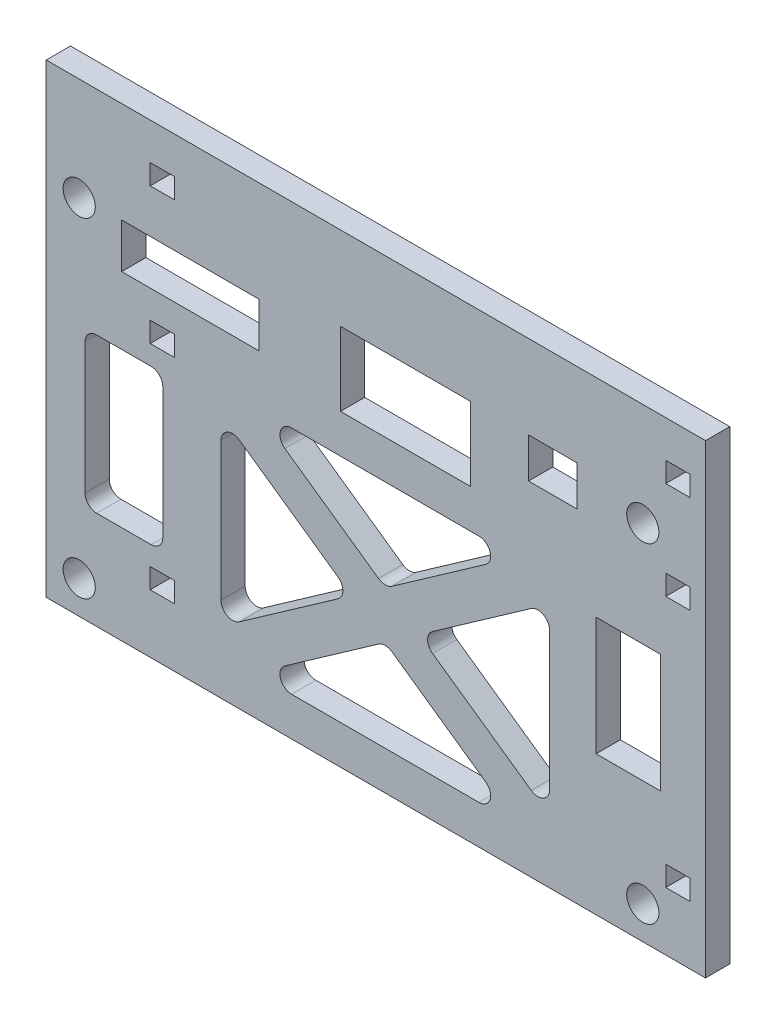
SolidWorks part; units mm, degrees
material "Beech"
ref_plane "Front Plane" through (0, 0, 0) normal (0, 0, 1) x (1, 0, 0)
ref_plane "Top Plane" through (0, 0, 0) normal (0, 1, 0) x (1, 0, 0)
ref_plane "Right Plane" through (0, 0, 0) normal (1, 0, 0) x (0, 0, -1)
sketch "Sketch1" plane through (0, 0, 0) normal (0, 0, 1) x (1, 0, 0)
  line L0 (-21.59, 0) -> (21.59, 0)
  line L44 (0, 14.605) -> (0, 24.13) construction
  line L46 (-21.59, 0) -> (-21.59, 30.48)
  line L47 (-21.59, 30.48) -> (21.59, 30.48)
  line L48 (21.59, 0) -> (21.59, 30.48)
  line L49 (-21.59, 12.7) -> (21.59, 12.7) construction
  circle A0 centre (17.4828, 2.159) radius 1.0541
  circle A1 centre (17.4828, 23.749) radius 1.0541
  circle A2 centre (-19.431, 2.159) radius 1.0541
  circle A3 centre (-19.431, 23.749) radius 1.0541
  point P0 (0, 0)
  point P56 (0, 12.7)
  point P60 (0, 30.48)
  dimension "D14" = 17.78
  dimension "D4" = 2.1082
  dimension "D2" = 12.7
  dimension "D3" = 2.159
  dimension "D12" = 43.18
  dimension "D5" = 2.159
  dimension "D6" = 2
  dimension "D7" = 2
extrude "Boss-Extrude1" add sketch "Sketch1" along normal blind 1.5875
fillet "Fillet7" [suppressed] radius 15.24
sketch "Sketch5" plane through (0, 0, 1.5875) normal (0, 0, 1) x (1, 0, 0)
  line L0 (-16.651, 23.878) -> (-16.651, 20.948) construction
  line L1 (-16.651, 20.948) -> (-7.651, 20.948) construction
  line L2 (-7.651, 20.948) -> (-7.651, 23.878) construction
  line L3 (-7.651, 23.878) -> (-16.651, 23.878) construction
  line L12 (6.1886, 20.184) -> (6.1886, 25.01) construction
  line L13 (6.1886, 25.01) -> (-2.3204, 25.01) construction
  line L14 (-2.3204, 25.01) -> (-2.3204, 20.184) construction
  line L15 (-2.3204, 20.184) -> (6.1886, 20.184) construction
  line L16 (13.1736, 22.3938) -> (13.1736, 25.01) construction
  line L17 (13.1736, 25.01) -> (9.9986, 25.01) construction
  line L18 (9.9986, 25.01) -> (9.9986, 22.3938) construction
  line L19 (9.9986, 22.3938) -> (13.1736, 22.3938) construction
  line L20 (14.4226, 16.8835) -> (14.4226, 9.1335) construction
  line L21 (14.4226, 9.1335) -> (18.6426, 9.1335) construction
  line L22 (18.6426, 9.1335) -> (18.6426, 16.8835) construction
  line L23 (18.6426, 16.8835) -> (14.4226, 16.8835) construction
  line L24 (-16.651, 23.878) -> (-16.651, 20.948)
  line L25 (-16.651, 20.948) -> (-7.651, 20.948)
  line L26 (-7.651, 20.948) -> (-7.651, 23.878)
  line L27 (-7.651, 23.878) -> (-16.651, 23.878)
  line L28 (6.1886, 20.184) -> (6.1886, 25.01)
  line L29 (6.1886, 25.01) -> (-2.3204, 25.01)
  line L30 (-2.3204, 25.01) -> (-2.3204, 20.184)
  line L31 (-2.3204, 20.184) -> (6.1886, 20.184)
  line L32 (13.1736, 22.3938) -> (13.1736, 25.01)
  line L33 (13.1736, 25.01) -> (9.9986, 25.01)
  line L34 (9.9986, 25.01) -> (9.9986, 22.3938)
  line L35 (9.9986, 22.3938) -> (13.1736, 22.3938)
  line L36 (14.4226, 16.8835) -> (14.4226, 9.1335)
  line L37 (14.4226, 9.1335) -> (18.6426, 9.1335)
  line L38 (18.6426, 9.1335) -> (18.6426, 16.8835)
  line L39 (18.6426, 16.8835) -> (14.4226, 16.8835)
extrude "Camera Cuts" cut sketch "Sketch5" against normal up to next
sketch "Sketch6" plane through (0, 0, 1.5875) normal (0, 0, 1) x (1, 0, 0)
  line L0 (11.3746, 4.0915) -> (-7.9365, 17.644)
  line L1 (11.3746, 2.54) -> (-10.1473, 2.54)
  line L2 (11.3746, 2.54) -> (11.3746, 17.644)
  line L3 (11.3746, 17.644) -> (-10.1473, 17.644)
  line L4 (-10.1473, 2.54) -> (-10.1473, 17.644)
  line L5 (11.3746, 2.54) -> (-10.1473, 17.644) construction
  line L6 (11.3746, 17.644) -> (-10.1473, 2.54) construction
  line L7 (9.1638, 2.54) -> (-10.1473, 16.0925)
  line L8 (9.1638, 17.644) -> (-10.1473, 4.0915)
  line L9 (11.3746, 16.0925) -> (-7.9365, 2.54)
  line L10 (10.645, 1.5005) -> (-10.8769, 16.6045) construction
  line L11 (12.1042, 16.6045) -> (-9.4177, 1.5005) construction
  line L12 (10.645, 18.6835) -> (-10.8769, 3.5795) construction
  line L13 (12.1042, 3.5795) -> (-9.4177, 18.6835) construction
  line L14 (-21.59, 0) -> (21.59, 0) construction
  line L15 (14.4226, 16.8835) -> (14.4226, 9.1335) construction
  line L16 (-2.3204, 20.184) -> (6.1886, 20.184) construction
  line L18 (-21.59, 0) -> (-21.59, 30.48) construction
  line L19 (-19.05, 6.4248) -> (-13.9573, 6.4248)
  line L20 (-19.05, 6.4248) -> (-19.05, 16.534)
  line L21 (-19.05, 16.534) -> (-13.9573, 16.534)
  line L22 (-13.9573, 6.4248) -> (-13.9573, 16.534)
  line L23 (-19.05, 6.4248) -> (-13.9573, 16.534) construction
  line L24 (-19.05, 16.534) -> (-13.9573, 6.4248) construction
  line L27 (-13.1953, 5.1548) -> (-13.1953, 3.834) construction
  line L28 (-14.7828, 17.804) -> (-13.1953, 17.804) construction
  line L29 (-14.7828, 5.1548) -> (-13.1953, 5.1548) construction
  point P0 (0.6137, 10.092)
  point P29 (-16.5036, 11.4794)
  dimension "D5" = 2.54
  dimension "D6" = 3.048
  dimension "D7" = 2.54
  dimension "D8" = 3.048
  dimension "D9" = 2.54
  dimension "D10" = 1.27
  dimension "D11" = 1.27
  dimension "D12" = 3.81
  dimension "D1" = 1.27
  dimension "D2" = 1.27
  dimension "D3" = 1.27
  dimension "D4" = 1.27
extrude "Weight Reduction Cuts" cut sketch "Sketch6" against normal blind 2.54 contours L7 L9 L1 | L2 L9 L0 | L8 L3 L0 | L8 L7 L4 | L19 L22 L21 L20
sketch "Sketch7" plane through (0, 0, 0) normal (0, 0, -1) x (-1, 0, 0)
  line L0 (13.1953, 28.0656) -> (13.1953, 26.7448) construction
  line L1 (13.1953, 26.7448) -> (14.7828, 26.7448) construction
  line L2 (14.7828, 26.7448) -> (14.7828, 28.0656) construction
  line L3 (14.7828, 28.0656) -> (13.1953, 28.0656) construction
  line L4 (13.1953, 19.1248) -> (13.1953, 17.804) construction
  line L5 (13.1953, 17.804) -> (14.7828, 17.804) construction
  line L6 (14.7828, 17.804) -> (14.7828, 19.1248) construction
  line L7 (14.7828, 19.1248) -> (13.1953, 19.1248) construction
  line L8 (13.1953, 5.1548) -> (13.1953, 3.834) construction
  line L9 (13.1953, 3.834) -> (14.7828, 3.834) construction
  line L10 (14.7828, 3.834) -> (14.7828, 5.1548) construction
  line L11 (14.7828, 5.1548) -> (13.1953, 5.1548) construction
  line L12 (-20.574, 5.1548) -> (-20.574, 3.834) construction
  line L13 (-20.574, 3.834) -> (-18.9865, 3.834) construction
  line L14 (-18.9865, 3.834) -> (-18.9865, 5.1548) construction
  line L15 (-18.9865, 5.1548) -> (-20.574, 5.1548) construction
  line L16 (-20.574, 21.6648) -> (-20.574, 20.344) construction
  line L17 (-20.574, 20.344) -> (-18.9865, 20.344) construction
  line L18 (-18.9865, 20.344) -> (-18.9865, 21.6648) construction
  line L19 (-18.9865, 21.6648) -> (-20.574, 21.6648) construction
  line L20 (-20.574, 28.0656) -> (-20.574, 26.7448) construction
  line L21 (-20.574, 26.7448) -> (-18.9865, 26.7448) construction
  line L22 (-18.9865, 26.7448) -> (-18.9865, 28.0656) construction
  line L23 (-18.9865, 28.0656) -> (-20.574, 28.0656) construction
  line L24 (13.1953, 28.0656) -> (13.1953, 26.7448)
  line L25 (13.1953, 26.7448) -> (14.7828, 26.7448)
  line L26 (14.7828, 26.7448) -> (14.7828, 28.0656)
  line L27 (14.7828, 28.0656) -> (13.1953, 28.0656)
  line L28 (13.1953, 19.1248) -> (13.1953, 17.804)
  line L29 (13.1953, 17.804) -> (14.7828, 17.804)
  line L30 (14.7828, 17.804) -> (14.7828, 19.1248)
  line L31 (14.7828, 19.1248) -> (13.1953, 19.1248)
  line L32 (13.1953, 5.1548) -> (13.1953, 3.834)
  line L33 (13.1953, 3.834) -> (14.7828, 3.834)
  line L34 (14.7828, 3.834) -> (14.7828, 5.1548)
  line L35 (14.7828, 5.1548) -> (13.1953, 5.1548)
  line L36 (-20.574, 5.1548) -> (-20.574, 3.834)
  line L37 (-20.574, 3.834) -> (-18.9865, 3.834)
  line L38 (-18.9865, 3.834) -> (-18.9865, 5.1548)
  line L39 (-18.9865, 5.1548) -> (-20.574, 5.1548)
  line L40 (-20.574, 21.6648) -> (-20.574, 20.344)
  line L41 (-20.574, 20.344) -> (-18.9865, 20.344)
  line L42 (-18.9865, 20.344) -> (-18.9865, 21.6648)
  line L43 (-18.9865, 21.6648) -> (-20.574, 21.6648)
  line L44 (-20.574, 28.0656) -> (-20.574, 26.7448)
  line L45 (-20.574, 26.7448) -> (-18.9865, 26.7448)
  line L46 (-18.9865, 26.7448) -> (-18.9865, 28.0656)
  line L47 (-18.9865, 28.0656) -> (-20.574, 28.0656)
extrude "Attachment Cuts" cut sketch "Sketch7" against normal up to next
fillet "Fillet8" radius 0.762 16 edges at (-10.1473, 4.0915, 0.7937) (-7.9365, 2.54, 0.7937) (9.1638, 2.54, 0.7937) (11.3746, 4.0915, 0.7937) (0.6137, 11.6435, 0.7937) (-7.9365, 17.644, 0.7937) (2.8245, 10.092, 0.7937) (0.6137, 8.5405, 0.7937) (-10.1473, 16.0925, 0.7937) (9.1638, 17.644, 0.7937) (-1.5972, 10.092, 0.7937) (11.3746, 16.0925, 0.7937) (-19.05, 16.534, 0.7937) (-19.05, 6.4248, 0.7937) (-13.9573, 6.4248, 0.7937) (-13.9573, 16.534, 0.7937)
